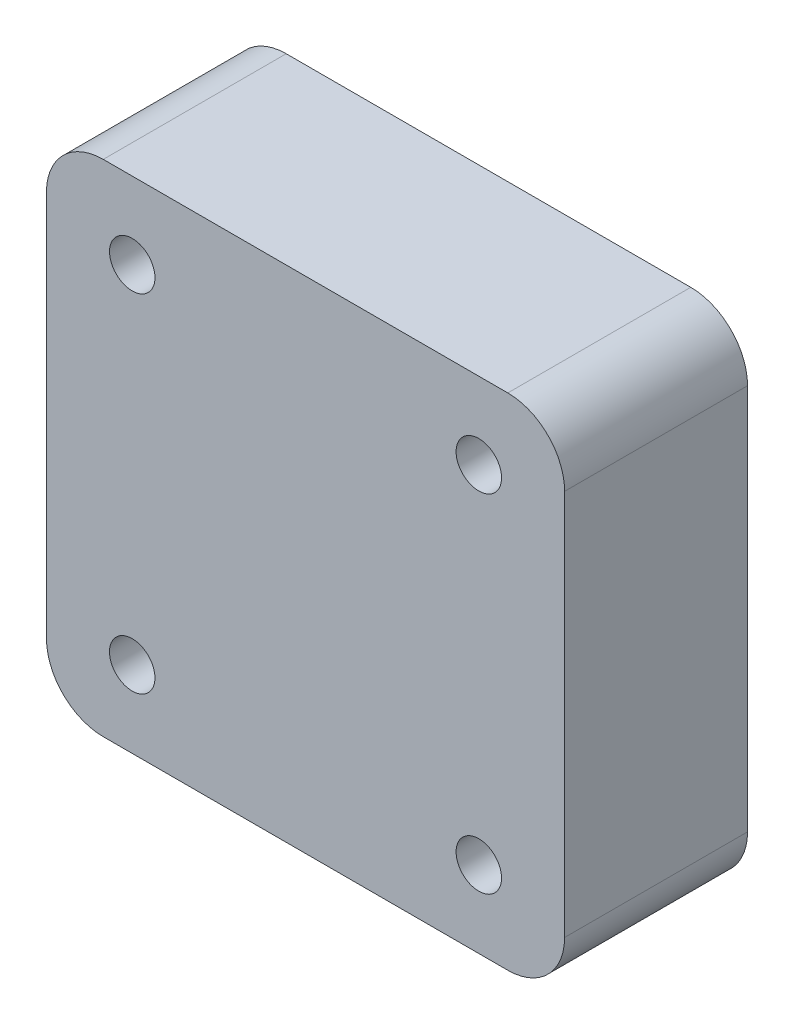
SolidWorks part; units mm, degrees
ref_plane "Front Plane" through (0, 0, 0) normal (0, 0, 1) x (1, 0, 0)
ref_plane "Top Plane" through (0, 0, 0) normal (0, 1, 0) x (1, 0, 0)
ref_plane "Right Plane" through (0, 0, 0) normal (1, 0, 0) x (0, 0, -1)
sketch "Sketch3" plane through (0, 0, 0) normal (0, 0, 1) x (1, 0, 0)
  line L0 (0, 0) -> (0, 50000) construction
  line L5 (-17.8, -22) -> (17.8, -22)
  line L6 (-22.8, -17) -> (-22.8, 17)
  line L7 (-17.8, 22) -> (17.8, 22)
  line L8 (22.8, -17) -> (22.8, 17)
  line L9 (-22.8, -22) -> (22.8, 22) construction
  line L10 (-22.8, 22) -> (22.8, -22) construction
  line L11 (0, 0) -> (50000, 0) construction
  circle A0 centre (-15.25, 15.25) radius 2
  circle A1 centre (15.25, 15.25) radius 2
  circle A2 centre (15.25, -15.25) radius 2
  circle A3 centre (-15.25, -15.25) radius 2
  arc A4 (17.8, -22) -> (22.8, -17) centre (17.8, -17) ccw
  arc A5 (17.8, 22) -> (22.8, 17) centre (17.8, 17) cw
  arc A6 (-22.8, 17) -> (-17.8, 22) centre (-17.8, 17) cw
  arc A7 (-17.8, -22) -> (-22.8, -17) centre (-17.8, -17) cw
  point P0 (0, 0)
  dimension "D3" = 4
  dimension "D6" = 5
  dimension "D1" = 45.6
  dimension "D2" = 44
  dimension "D4" = 30.5
  dimension "D5" = 30.5
extrude "Boss-Extrude1" add sketch "Sketch3" along normal blind 16.1
